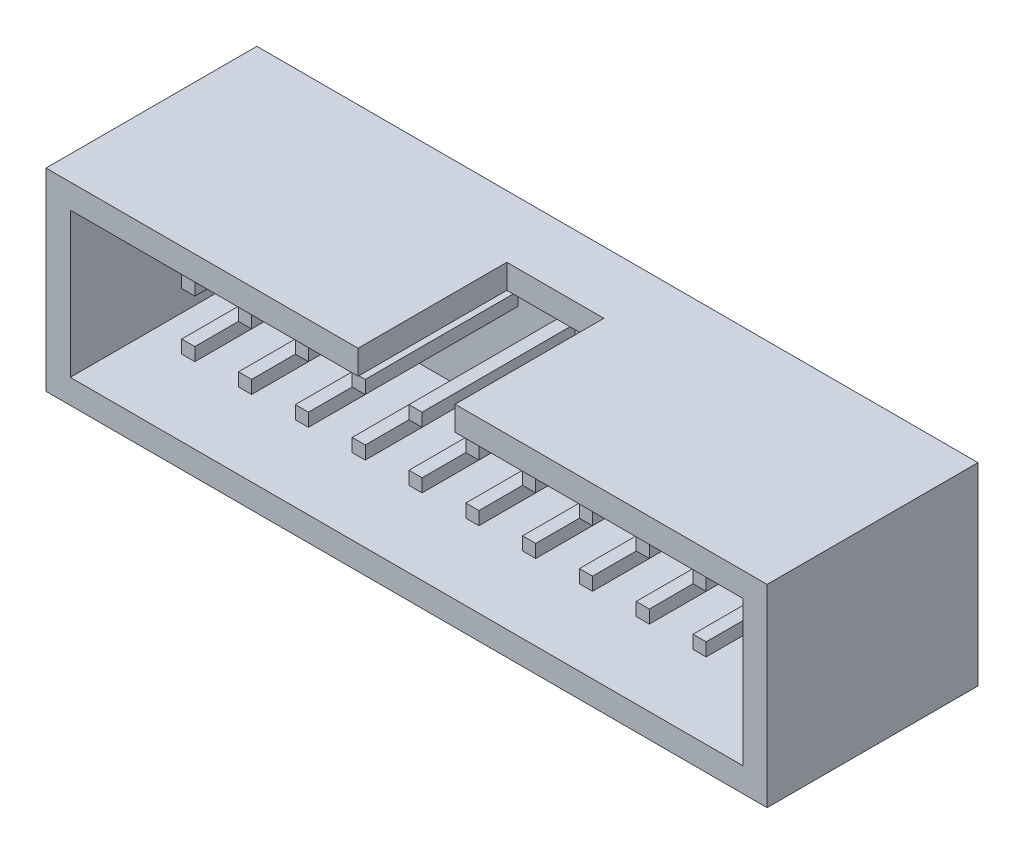
SolidWorks part; units mm, degrees
ref_plane "Płaszczyzna przednia" through (0, 0, 0) normal (0, 0, 1) x (1, 0, 0)
ref_plane "Płaszczyzna górna" through (0, 0, 0) normal (0, 1, 0) x (1, 0, 0)
ref_plane "Płaszczyzna prawa" through (0, 0, 0) normal (1, 0, 0) x (0, 0, -1)
sketch "Szkic1" plane through (0, 0, 0) normal (0, 0, 1) x (1, 0, 0)
  line L1 (-16.5, 4.425) -> (16.5, 4.425)
  line L2 (-16.5, 4.425) -> (-16.5, -4.425)
  line L3 (-16.5, -4.425) -> (16.5, -4.425)
  line L4 (16.5, 4.425) -> (16.5, -4.425)
  line L5 (-16.5, 4.425) -> (16.5, -4.425) construction
  line L6 (-16.5, -4.425) -> (16.5, 4.425) construction
  point P0 (0, 0)
  dimension "D1" = 33
  dimension "D2" = 8.85
extrude "Dodanie-wyciągnięcie1" add sketch "Szkic1" along normal blind 9.65
shell "Skorupa1" thickness 1.11
sketch "Szkic2" plane through (0, 4.425, 0) normal (0, 1, 0) x (1, 0, 0)
  line L0 (16.5, -9.65) -> (-16.5, -9.65) construction
  line L1 (-2.22, -9.65) -> (2.22, -9.65)
  line L2 (-2.22, -9.65) -> (-2.22, -2.84)
  line L3 (-2.22, -2.84) -> (2.22, -2.84)
  line L4 (2.22, -9.65) -> (2.22, -2.84)
  point P6 (0, -9.65)
  dimension "D1" = 4.44
  dimension "D2" = 6.81
extrude "Wytnij-wyciągnięcie1" cut sketch "Szkic2" against normal up to next
sketch "Szkic3" plane through (0, 0, 1.11) normal (0, 0, 1) x (1, 0, 0)
  line L0 (-15.39, 3.315) -> (-15.39, -3.315) construction
  line L1 (-11.83, 1.815) -> (-11.23, 1.815)
  line L2 (-11.83, 1.815) -> (-11.83, 1.215)
  line L3 (-11.83, 1.215) -> (-11.23, 1.215)
  line L4 (-11.23, 1.815) -> (-11.23, 1.215)
  line L5 (15.39, 3.315) -> (-15.39, 3.315) construction
  line L6 (-9.23, 1.815) -> (-9.23, 1.215)
  line L7 (-9.23, 1.215) -> (-8.63, 1.215)
  line L8 (-8.63, 1.815) -> (-8.63, 1.215)
  line L9 (-9.23, 1.815) -> (-8.63, 1.815)
  line L10 (-6.63, 1.815) -> (-6.63, 1.215)
  line L11 (-6.63, 1.215) -> (-6.03, 1.215)
  line L12 (-6.03, 1.815) -> (-6.03, 1.215)
  line L13 (-6.63, 1.815) -> (-6.03, 1.815)
  line L14 (-4.03, 1.815) -> (-4.03, 1.215)
  line L15 (-4.03, 1.215) -> (-3.43, 1.215)
  line L16 (-3.43, 1.815) -> (-3.43, 1.215)
  line L17 (-4.03, 1.815) -> (-3.43, 1.815)
  line L18 (-1.43, 1.815) -> (-1.43, 1.215)
  line L19 (-1.43, 1.215) -> (-0.83, 1.215)
  line L20 (-0.83, 1.815) -> (-0.83, 1.215)
  line L21 (-1.43, 1.815) -> (-0.83, 1.815)
  line L22 (1.17, 1.815) -> (1.17, 1.215)
  line L23 (1.17, 1.215) -> (1.77, 1.215)
  line L24 (1.77, 1.815) -> (1.77, 1.215)
  line L25 (1.17, 1.815) -> (1.77, 1.815)
  line L26 (3.77, 1.815) -> (3.77, 1.215)
  line L27 (3.77, 1.215) -> (4.37, 1.215)
  line L28 (4.37, 1.815) -> (4.37, 1.215)
  line L29 (3.77, 1.815) -> (4.37, 1.815)
  line L30 (6.37, 1.815) -> (6.37, 1.215)
  line L31 (6.37, 1.215) -> (6.97, 1.215)
  line L32 (6.97, 1.815) -> (6.97, 1.215)
  line L33 (6.37, 1.815) -> (6.97, 1.815)
  line L34 (8.97, 1.815) -> (8.97, 1.215)
  line L35 (8.97, 1.215) -> (9.57, 1.215)
  line L36 (9.57, 1.815) -> (9.57, 1.215)
  line L37 (8.97, 1.815) -> (9.57, 1.815)
  line L38 (11.57, 1.815) -> (11.57, 1.215)
  line L39 (11.57, 1.215) -> (12.17, 1.215)
  line L40 (12.17, 1.815) -> (12.17, 1.215)
  line L41 (11.57, 1.815) -> (12.17, 1.815)
  line L42 (-9.23, -0.785) -> (-9.23, -1.385)
  line L43 (-9.23, -1.385) -> (-8.63, -1.385)
  line L44 (-8.63, -0.785) -> (-8.63, -1.385)
  line L45 (-9.23, -0.785) -> (-8.63, -0.785)
  line L46 (-6.63, -0.785) -> (-6.63, -1.385)
  line L47 (-6.63, -1.385) -> (-6.03, -1.385)
  line L48 (-6.03, -0.785) -> (-6.03, -1.385)
  line L49 (-6.63, -0.785) -> (-6.03, -0.785)
  line L50 (-4.03, -0.785) -> (-4.03, -1.385)
  line L51 (-4.03, -1.385) -> (-3.43, -1.385)
  line L52 (-3.43, -0.785) -> (-3.43, -1.385)
  line L53 (-4.03, -0.785) -> (-3.43, -0.785)
  line L54 (-1.43, -0.785) -> (-1.43, -1.385)
  line L55 (-1.43, -1.385) -> (-0.83, -1.385)
  line L56 (-0.83, -0.785) -> (-0.83, -1.385)
  line L57 (-1.43, -0.785) -> (-0.83, -0.785)
  line L58 (1.17, -0.785) -> (1.17, -1.385)
  line L59 (1.17, -1.385) -> (1.77, -1.385)
  line L60 (1.77, -0.785) -> (1.77, -1.385)
  line L61 (1.17, -0.785) -> (1.77, -0.785)
  line L62 (3.77, -0.785) -> (3.77, -1.385)
  line L63 (3.77, -1.385) -> (4.37, -1.385)
  line L64 (4.37, -0.785) -> (4.37, -1.385)
  line L65 (3.77, -0.785) -> (4.37, -0.785)
  line L66 (6.37, -0.785) -> (6.37, -1.385)
  line L67 (6.37, -1.385) -> (6.97, -1.385)
  line L68 (6.97, -0.785) -> (6.97, -1.385)
  line L69 (6.37, -0.785) -> (6.97, -0.785)
  line L70 (8.97, -0.785) -> (8.97, -1.385)
  line L71 (8.97, -1.385) -> (9.57, -1.385)
  line L72 (9.57, -0.785) -> (9.57, -1.385)
  line L73 (8.97, -0.785) -> (9.57, -0.785)
  line L74 (11.57, -0.785) -> (11.57, -1.385)
  line L75 (11.57, -1.385) -> (12.17, -1.385)
  line L76 (12.17, -0.785) -> (12.17, -1.385)
  line L77 (11.57, -0.785) -> (12.17, -0.785)
  line L78 (-11.83, -0.785) -> (-11.83, -1.385)
  line L79 (-11.83, -1.385) -> (-11.23, -1.385)
  line L80 (-11.23, -0.785) -> (-11.23, -1.385)
  line L81 (-11.83, -0.785) -> (-11.23, -0.785)
  line L82 (-11.83, 1.815) -> (-9.23, 1.815) construction
  dimension "D1" = 0.6
  dimension "D2" = 3.56
  dimension "D3" = 1.5
  dimension "D6" = 2.6
  dimension "D4" = 10
  dimension "D5" = 2
extrude "Dodanie-wyciągnięcie2" add sketch "Szkic3" along normal blind 7
